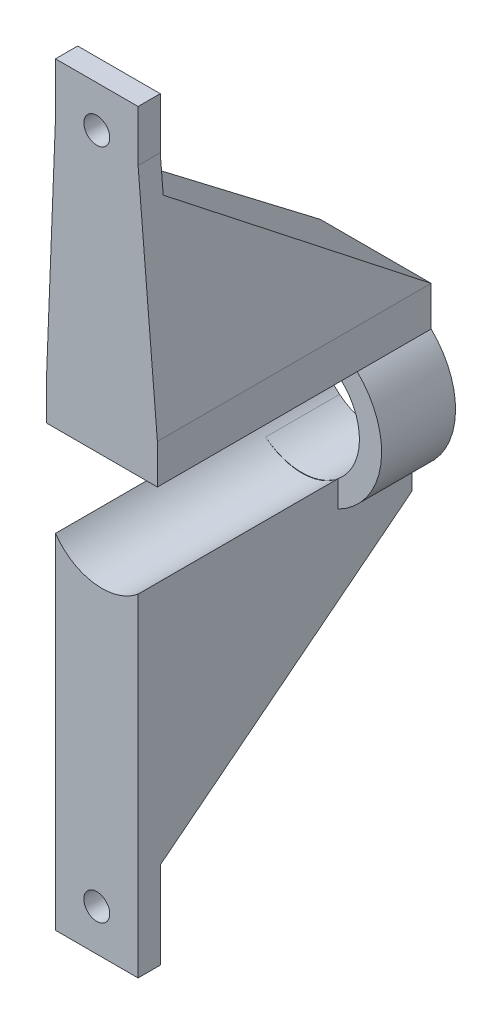
SolidWorks part; units mm, degrees
ref_plane "Front Plane" through (0, 0, 0) normal (0, 0, 1) x (1, 0, 0)
ref_plane "Top Plane" through (0, 0, 0) normal (0, 1, 0) x (1, 0, 0)
ref_plane "Right Plane" through (0, 0, 0) normal (1, 0, 0) x (0, 0, -1)
sketch "Sketch1" plane through (0, 0, 0) normal (0, 0, 1) x (1, 0, 0)
  line L0 (4.5, 6.6144) -> (4.5, 10.3644)
  line L1 (4.5, 10.3644) -> (-4.5, 10.3644)
  line L2 (-4.5, 10.3644) -> (-4.5, 6.6144)
  line L3 (4.5, 6.6144) -> (-4.5, 6.6144) construction
  arc A0 (4.5, 6.6144) -> (-4.5, 6.6144) centre (0, 0.2434) cw
  dimension "D1" = 7.8
  dimension "D2" = 3.75
extrude "Extrude-Thin1" add sketch "Sketch1" against normal blind 10 thin contours A0 L2 L1 L0
sketch "Sketch2" plane through (0, 0, -10) normal (0, 0, -1) x (-1, 0, 0)
  line L0 (0, -1.75) -> (0, 1.75)
  line L1 (0, 1.75) -> (17.8241, 1.75)
  line L2 (17.8241, 1.75) -> (17.8241, -1.75)
  line L3 (17.8241, -1.75) -> (0, -1.75)
  point P5 (0, 0)
  dimension "D1" = 3.5
extrude "Cut-Extrude1" cut sketch "Sketch2" against normal blind 10
sketch "Sketch3" plane through (0, 0, 0) normal (0, 0, 1) x (1, 0, 0)
  line L0 (-10.6145, -1.75) -> (-7.541, -1.75) construction
  line L5 (-7.6531, 1.75) -> (-16.6531, 1.75)
  line L6 (-7.6531, 1.75) -> (-7.6531, 4.75)
  line L7 (-7.6531, 4.75) -> (-16.6531, 4.75)
  line L8 (-16.6531, 1.75) -> (-16.6531, 4.75)
  line L9 (-7.541, -1.75) -> (-16.541, -1.75)
  line L10 (-7.541, -1.75) -> (-7.541, -4.75)
  line L11 (-7.541, -4.75) -> (-16.541, -4.75)
  line L12 (-16.541, -1.75) -> (-16.541, -4.75)
  dimension "D3" = 9
  dimension "D4" = 9
  dimension "D7" = 3
  dimension "D8" = 3
extrude "Boss-Extrude1" add sketch "Sketch3" against normal blind 10
sketch "Sketch4" plane through (0, 4.75, 0) normal (0, 1, 0) x (1, 0, 0)
  line L0 (-16.6531, 10) -> (-9.8148, 0) construction
  line L3 (0, 0) -> (0, 20.7946) construction
  line L4 (-13.2339, 5) -> (0, 5) construction
  line L6 (-16.6531, 0) -> (-9.8148, 10) construction
  circle A1 centre (-13.2339, 5) radius 1.75
  dimension "D2" = 3.5
extrude "Cut-Extrude2" cut sketch "Sketch4" against normal blind 10
sketch "Sketch5" plane through (0, 0, 0) normal (0, 0, 1) x (1, 0, 0)
  line L0 (7.5, 8.0145) -> (7.5, 13.3644) construction
  line L1 (7.5, 13.3644) -> (-7.5, 13.3644) construction
  line L2 (-7.5, 13.3644) -> (-7.5, 8.0145) construction
  line L3 (7.5, 8.0145) -> (7.5, 13.3644)
  line L4 (7.5, 13.3644) -> (-7.5, 13.3644)
  line L5 (-7.5, 13.3644) -> (-7.5, 8.0145)
  line L6 (-7.5, 8.0145) -> (7.5, 8.0145)
extrude "Boss-Extrude2" add sketch "Sketch5" along normal up to vertex (27.0318 mm away)
sketch "Sketch6" plane through (0, 0, -10) normal (0, 0, -1) x (-1, 0, 0)
  line L0 (4.5, 10.3644) -> (4.5, 6.6144) construction
  line L1 (-4.5, 10.3644) -> (4.5, 10.3644) construction
  line L2 (-4.5, 6.6144) -> (-4.5, 10.3644) construction
  line L3 (4.5, 10.3644) -> (4.5, 6.6144)
  line L4 (-4.5, 10.3644) -> (4.5, 10.3644)
  line L5 (-4.5, 6.6144) -> (-4.5, 10.3644)
  line L6 (-4.5, 6.6144) -> (4.5, 6.6144)
extrude "Cut-Extrude3" cut sketch "Sketch6" against normal blind 13
sketch "Sketch7" plane through (-7.5, 0, 0) normal (-1, 0, 0) x (0, 0, 1)
  line L0 (27.0318, 13.3644) -> (-10, 13.3644)
  line L1 (-10, 13.3644) -> (27.0318, 13.3644) construction
  line L2 (27.0318, 13.3644) -> (27.0318, 51.2942)
  line L3 (27.0318, 51.2942) -> (24.0318, 51.2942)
  line L4 (24.0318, 51.2942) -> (24.0318, 39.6099)
  line L5 (24.0318, 39.6099) -> (-10, 13.3644)
  line L7 (-10, 13.3644) -> (-10, 8.0145) construction
  dimension "D1" = 3
extrude "Boss-Extrude3" add sketch "Sketch7" against normal up to vertex (15 mm away) contours L5 L0 L2 L3 L4
sketch "Sketch8" plane through (0, 0, -10) normal (0, 0, -1) x (-1, 0, 0)
  line L0 (6.2823, 44.3657) -> (6.2823, 47.053) construction
  line L1 (-4.8875, 47.053) -> (-4.8875, 44.3657) construction
  line L2 (6.2823, 44.3657) -> (6.2823, 47.053)
  line L3 (-4.8875, 47.053) -> (-4.8875, 44.3657)
  line L4 (-7.5, 51.2942) -> (-4.8875, 51.2942)
  line L5 (-4.8875, 51.2942) -> (-4.8875, 47.053)
  line L6 (-4.8875, 44.3657) -> (-7.5, 13.3644)
  line L7 (7.5, 51.2942) -> (6.2823, 51.2942)
  line L8 (6.2823, 51.2942) -> (6.2823, 47.053)
  line L9 (-7.5, 51.2942) -> (-7.5, 39.6099)
  line L10 (-7.5, 39.6099) -> (-7.5, 13.3644)
  line L11 (7.5, 39.6099) -> (7.5, 13.3644)
  line L12 (7.5, 51.2942) -> (7.5, 39.6099)
  line L13 (6.2823, 44.3657) -> (7.5, 13.3644)
  circle A0 centre (0.6974, 45.7094) radius 1.75
  dimension "D1" = 3.5
extrude "Cut-Extrude8" cut sketch "Sketch8" against normal up to surface (37.0318 mm away) up to face at (0, 29.6543, 27.0318)
sketch "Sketch11" plane through (0, 0, -10) normal (0, 0, -1) x (-1, 0, 0)
  line L0 (-4.8875, -46.5663) -> (-4.8875, -43.879) construction
  line L1 (6.2823, -43.879) -> (6.2823, -46.5663) construction
  line L2 (6.2823, -43.879) -> (6.2823, -46.5663)
  line L3 (-4.8875, -46.5663) -> (-4.8875, -43.879)
  line L4 (-4.8875, -43.879) -> (-4.8875, -5.8355)
  line L7 (6.2823, -43.879) -> (6.2823, -4.2981)
  line L8 (2.041, -50.8075) -> (-0.6463, -50.8075) construction
  line L9 (2.041, -50.8075) -> (-0.6463, -50.8075)
  line L10 (-4.8875, -46.5663) -> (-4.8875, -50.8075)
  line L11 (-4.8875, -50.8075) -> (-0.6463, -50.8075)
  line L12 (2.041, -50.8075) -> (6.2823, -50.8075)
  line L13 (6.2823, -50.8075) -> (6.2823, -46.5663)
  arc A0 (7.6531, 1.75) -> (4.5, 6.6144) centre (0, 0.2434) ccw construction
  arc A2 (-4.8875, -5.8355) -> (6.2823, -4.2981) centre (0, 0) ccw
extrude "Boss-Extrude4" add sketch "Sketch11" against normal up to vertex (37.0318 mm away)
sketch "Sketch12" plane through (-6.2823, 0, 0) normal (1, 0, 0) x (0, 0, -1)
  line L0 (10, -12.3094) -> (10, -50.8075)
  line L1 (10, -50.8075) -> (10, -8.5415) construction
  line L3 (10, -50.8075) -> (-24.0318, -50.8075)
  line L4 (-27.0318, -50.8075) -> (10, -50.8075) construction
  line L6 (-24.0318, -50.8075) -> (-24.0318, -39.0626)
  line L7 (-24.0318, -39.0626) -> (10, -12.3094)
  line L8 (-27.0318, -50.8075) -> (-27.0318, -4.2981) construction
  dimension "D1" = 3
extrude "Cut-Extrude6" cut sketch "Sketch12" along normal up to surface (11.1698 mm away) up to face at (4.8875, 47.83, 25.5318)
sketch "Sketch13" plane through (0, 0, 27.0318) normal (0, 0, 1) x (1, 0, 0)
  circle A0 centre (-0.6974, -45.2226) radius 1.75
  dimension "D1" = 3.5
extrude "Cut-Extrude9" cut sketch "Sketch13" against normal up to surface (3 mm away) up to face at (-0.6974, -44.9351, 24.0318)
